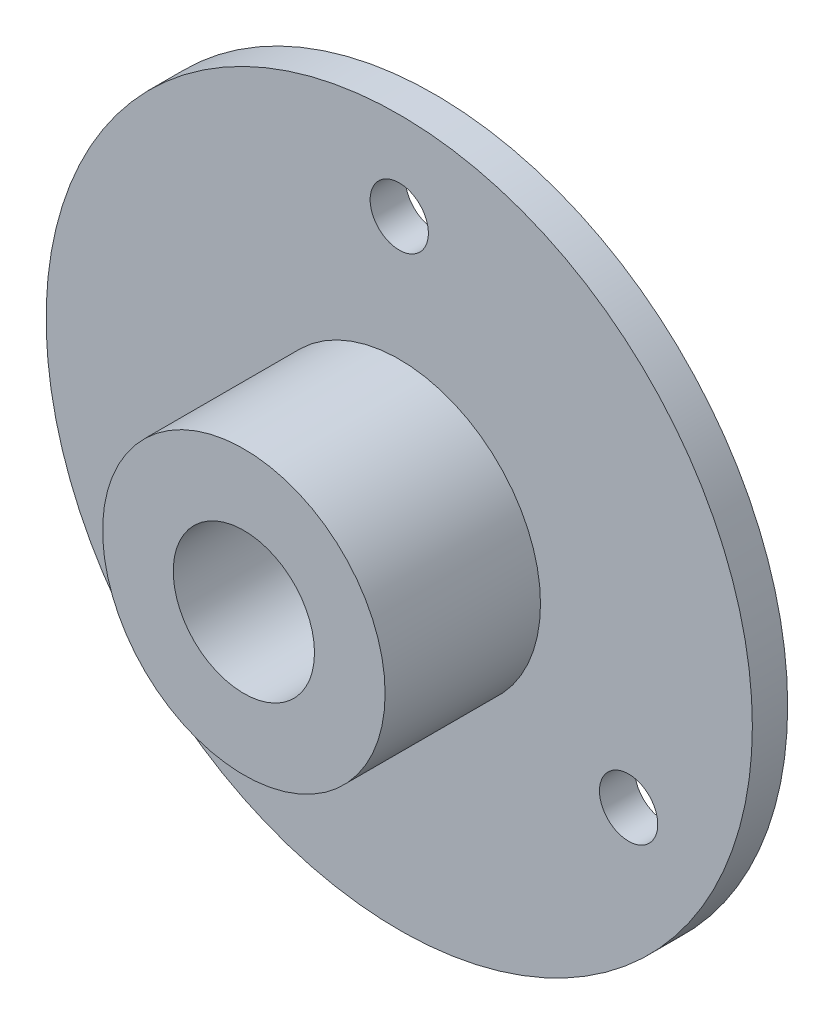
SolidWorks part; units mm, degrees
ref_plane "Front" through (0, 0, 0) normal (0, 0, 1) x (1, 0, 0)
ref_plane "Top" through (0, 0, 0) normal (0, 1, 0) x (1, 0, 0)
ref_plane "Right" through (0, 0, 0) normal (1, 0, 0) x (0, 0, -1)
sketch "草图1" plane through (0, 0, 0) normal (0, 0, 1) x (1, 0, 0)
  circle A0 centre (0, 0) radius 20
extrude "凸台-拉伸1" add sketch "草图1" along normal blind 2
sketch "草图2" plane through (0, 0, 2) normal (0, 0, 1) x (1, 0, 0)
  circle A0 centre (0, 0) radius 8
extrude "凸台-拉伸2" add sketch "草图2" along normal blind 8.8
sketch "草图3" plane through (0, 0, 10.8) normal (0, 0, 1) x (1, 0, 0)
  circle A0 centre (0, 0) radius 4
  dimension "D1" = 8
extrude "切除-拉伸1" cut sketch "草图3" against normal through all
sketch "草图4" plane through (0, 0, 0) normal (0, 0, -1) x (-1, 0, 0)
  circle A0 centre (0, 15) radius 1.65
  dimension "D1" = 15
  dimension "D2" = 3.3
extrude "切除-拉伸2" cut sketch "草图4" against normal through all
pattern_circular "阵列(圆周)1" count 3 over 360 about axis through (0, 0, 0) along (0, 0, 1) of "切除-拉伸2"
